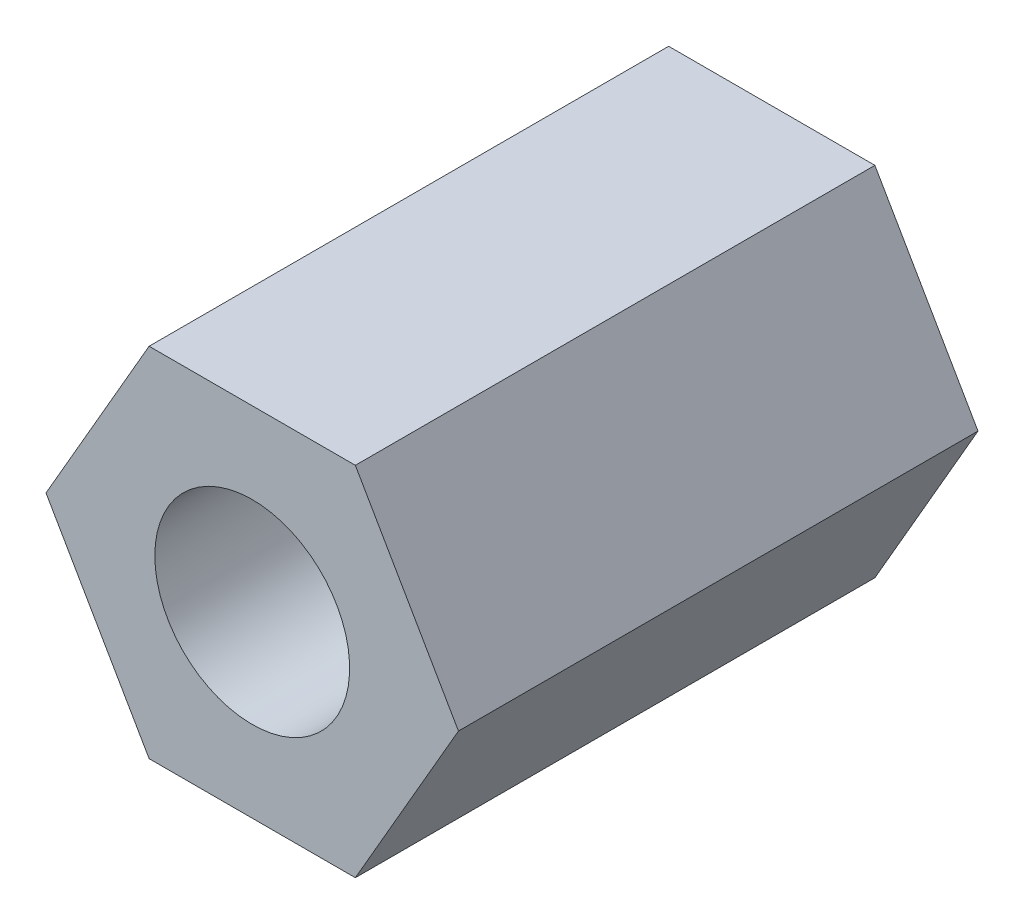
SolidWorks part; units mm, degrees
ref_plane "Face" through (0, 0, 0) normal (0, 0, 1) x (1, 0, 0)
ref_plane "Dessus" through (0, 0, 0) normal (0, 1, 0) x (1, 0, 0)
ref_plane "Droite" through (0, 0, 0) normal (1, 0, 0) x (0, 0, -1)
sketch "Esquisse1" plane through (0, 0, 0) normal (0, 0, 1) x (1, 0, 0)
  line L1 (1.5877, 2.75) -> (-1.5877, 2.75)
  line L2 (-1.5877, 2.75) -> (-3.1754, 0)
  line L3 (-3.1754, 0) -> (-1.5877, -2.75)
  line L4 (-1.5877, -2.75) -> (1.5877, -2.75)
  line L5 (1.5877, -2.75) -> (3.1754, 0)
  line L6 (3.1754, 0) -> (1.5877, 2.75)
  circle A0 centre (0, 0) radius 2.75 construction
  dimension "D1" = 5.5
extrude "Base-Extrusion" add sketch "Esquisse1" along normal blind 8
sketch "Esquisse3" plane through (0, 0, 0) normal (0, 0, -1) x (-1, 0, 0)
  circle A0 centre (0, 0) radius 1.5
extrude "Enlèv. mat.-Extru.1" cut sketch "Esquisse3" against normal through all
